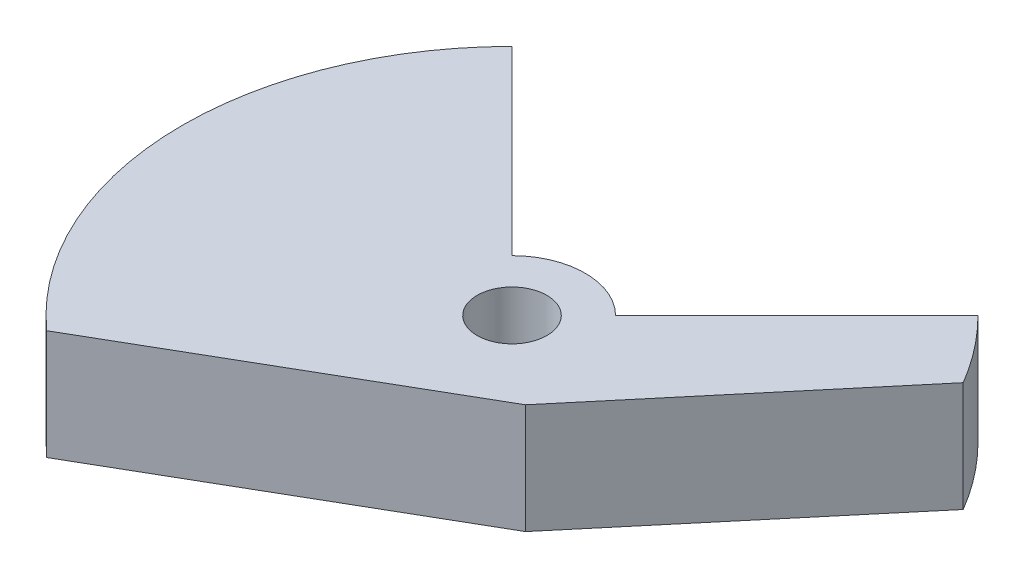
SolidWorks part; units mm, degrees
material "ABS"
ref_plane "Front Plane" through (0, 0, 0) normal (0, 0, 1) x (1, 0, 0)
ref_plane "Top Plane" through (0, 0, 0) normal (0, 1, 0) x (1, 0, 0)
ref_plane "Right Plane" through (0, 0, 0) normal (1, 0, 0) x (0, 0, -1)
sketch "Sketch1" plane through (0, 0, 0) normal (0, 1, 0) x (1, 0, 0)
  line L0 (-31.8198, 31.8198) -> (-7.0711, 7.0711)
  line L1 (7.0711, 7.0711) -> (31.8198, 31.8198)
  line L2 (0, 0) -> (0, 20) construction
  line L3 (0, 0) -> (-7.0711, 7.0711) construction
  line L4 (7.0711, 7.0711) -> (0, 0) construction
  arc A0 (-31.8198, 31.8198) -> (31.8198, 31.8198) centre (0, 0) ccw
  circle A1 centre (0, 0) radius 4.7625
  arc A2 (7.0711, 7.0711) -> (-7.0711, 7.0711) centre (0, 0) ccw
  dimension "D1" = 9.525
  dimension "D2" = 90
  dimension "D3" = 20
  dimension "D4" = 45
extrude "Boss-Extrude1" add sketch "Sketch1" along normal blind 15
sketch "Sketch2" plane through (0, 15, 0) normal (0, 1, 0) x (1, 0, 0)
  line L0 (4.0536, 2.5) -> (4.0536, -2.5)
  arc A0 (4.0536, -2.5) -> (4.0536, 2.5) centre (0, 0) ccw
  circle A1 centre (0, 0) radius 4.7625 construction
  dimension "D1" = 5
extrude "Shaft D" [suppressed] add sketch "Sketch2" against normal up to surface (10 mm away)
sketch "Sketch3" plane through (0, 15, 0) normal (0, 1, 0) x (1, 0, 0)
  line L0 (-31.8198, 31.8198) -> (-27.5772, 36.0624)
  line L1 (-27.5772, 36.0624) -> (-27.5772, 27.5772)
  line L2 (-7.0711, 7.0711) -> (-31.8198, 31.8198) construction
  line L3 (-27.5772, 27.5772) -> (-31.8198, 31.8198)
  line L4 (0, 0) -> (0, 30.6174) construction
  line L5 (27.5772, 27.5772) -> (31.8198, 31.8198)
  line L6 (27.5772, 36.0624) -> (27.5772, 27.5772)
  line L7 (31.8198, 31.8198) -> (27.5772, 36.0624)
  dimension "D1" = 6
extrude "Boss-Extrude2" [suppressed] add sketch "Sketch3" against normal up to surface (15 mm away)
sketch "Sketch4" plane through (0, 15, 0) normal (0, 1, 0) x (1, 0, 0)
  line L0 (-148.943, 0) -> (142.5774, 0) construction
  line L1 (0, 0) -> (-107.5774, -62.1099) construction
  line L2 (0, 0) -> (49.4281, -41.4751) construction
  line L8 (0, 0) -> (41.4751, 49.4281) construction
  line L9 (0, 0) -> (62.1099, -107.5774) construction
  line L10 (-107.5774, -62.1099) -> (62.1099, -107.5774) construction
  line L11 (41.4751, 49.4281) -> (49.4281, -41.4751) construction
  line L14 (11.4907, -9.6418) -> (45.5038, 30.8934)
  line L15 (11.4907, -9.6418) -> (-38.9929, -38.7885)
  arc A2 (-38.9929, -38.7885) -> (45.5038, 30.8934) centre (0, 0) ccw
  dimension "D4" = 55
  dimension "D1" = 40
  dimension "D3" = 30
  dimension "D5" = 15
extrude "Cut-Extrude1" cut sketch "Sketch4" against normal through all
